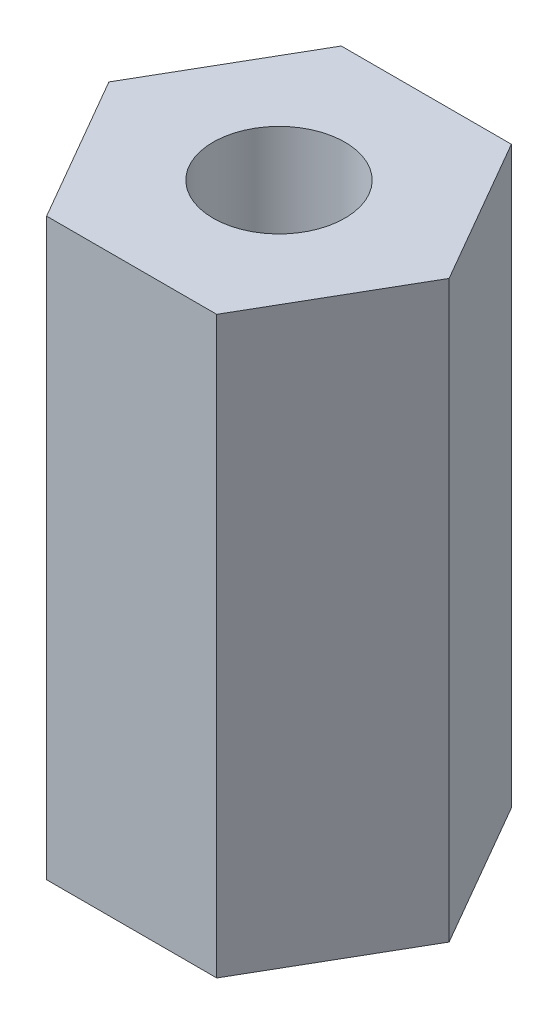
SolidWorks part; units mm, degrees
ref_plane "Front" through (0, 0, 0) normal (0, 0, 1) x (1, 0, 0)
ref_plane "Top" through (0, 0, 0) normal (0, 1, 0) x (1, 0, 0)
ref_plane "Right" through (0, 0, 0) normal (1, 0, 0) x (0, 0, -1)
sketch "Sketch1" plane through (0, 0, 0) normal (0, 1, 0) x (1, 0, 0)
  line L1 (3.2262, 0) -> (1.6131, 2.794)
  line L2 (1.6131, 2.794) -> (-1.6131, 2.794)
  line L3 (-1.6131, 2.794) -> (-3.2262, 0)
  line L4 (-3.2262, 0) -> (-1.6131, -2.794)
  line L5 (-1.6131, -2.794) -> (1.6131, -2.794)
  line L6 (1.6131, -2.794) -> (3.2262, 0)
  circle A0 centre (0, 0) radius 2.794 construction
  dimension "D1" = 5.588
extrude "Boss-Extrude1" add sketch "Sketch1" along normal blind 10.9
hole_wizard "M3x0.5 Tapped Hole1" positions "Sketch2" profile "Sketch3" tap size "M3x0.5" standard "ANSI Metric"
sketch "Sketch2" plane through (0, 10.9, 0) normal (0, 1, 0) x (1, 0, 0)
  line L0 (-1.6131, 2.794) -> (0, 0) construction
  line L1 (0, 0) -> (1.6131, -2.794) construction
  line L2 (-1.6131, -2.794) -> (1.6131, -2.794) construction
  line L3 (1.6131, -2.794) -> (3.2262, 0) construction
  point P0 (0, 0)
sketch "Sketch3" plane through (0, 10.9, 0) normal (1, 0, 0) x (0, 0, 1)
  line L0 (0, 0) -> (0, 20.7511)
  line L1 (0, 20.7511) -> (1.25, 20)
  line L2 (1.25, 20) -> (1.25, 0)
  line L5 (1.25, 0) -> (0, 0)
  line L10 (0, 20.7511) -> (-1.25, 20) construction
  line L11 (0, -6.35) -> (0, 107.95) construction
  dimension "Tap Drill Dia." = 2.5
  dimension "Tap Drill Depth" = 20
  dimension "Drill Angle" = 118
cosmetic thread "Hole Thread1"
